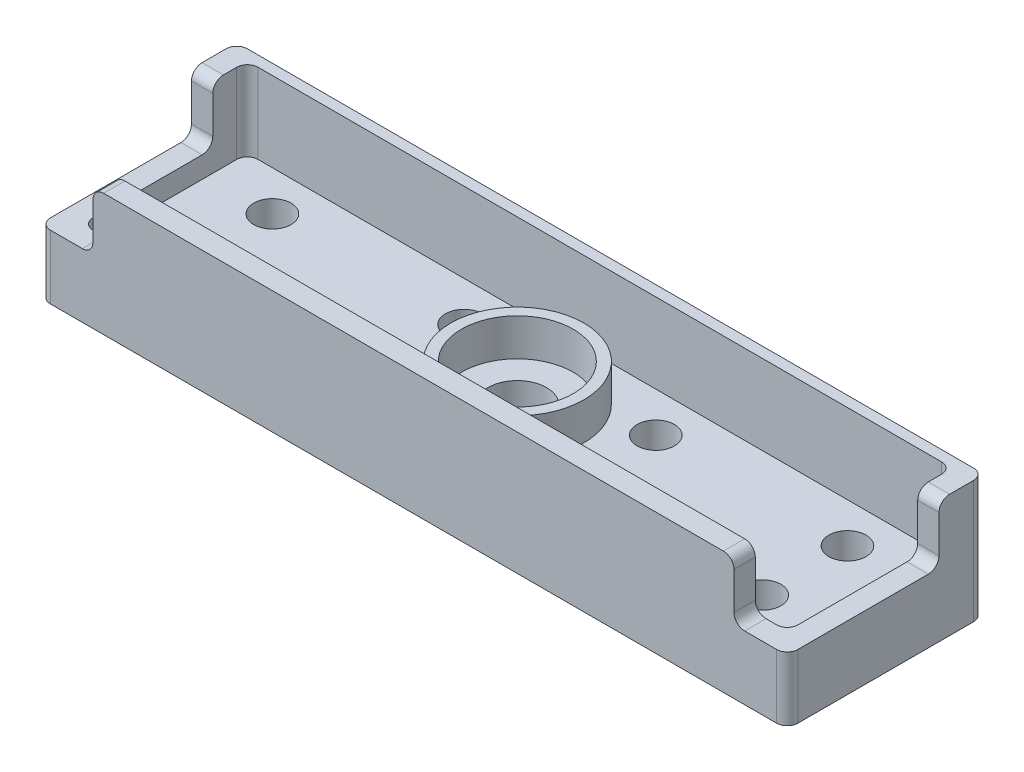
SolidWorks part; units mm, degrees
material "Delrin 2700 NC010, Low Viscosity Acetal Copolymer (SS)"
ref_plane "Front Plane" through (0, 0, 0) normal (0, 0, 1) x (1, 0, 0)
ref_plane "Top Plane" through (0, 0, 0) normal (0, 1, 0) x (1, 0, 0)
ref_plane "Right Plane" through (0, 0, 0) normal (1, 0, 0) x (0, 0, -1)
sketch "Sketch1" plane through (0, 0, 0) normal (0, 1, 0) x (1, 0, 0)
  line L1 (-35.1, -9.25) -> (0, -9.25)
  line L2 (-35.1, -9.25) -> (-35.1, 9.25)
  line L3 (-35.1, 9.25) -> (0, 9.25)
  line L4 (0, -9.25) -> (0, 9.25)
  line L5 (-35.1, -9.25) -> (0, 9.25) construction
  line L6 (-35.1, 9.25) -> (0, -9.25) construction
  point P0 (-17.55, 0)
  point P8 (0, 0)
  dimension "D1" = 35.1
  dimension "D2" = 18.5
extrude "Boss-Extrude1" add sketch "Sketch1" along normal blind 11.5
shell "Shell1" [suppressed] thickness 1
sketch "Sketch7" plane through (0, 11.5, 0) normal (0, 1, 0) x (1, 0, 0)
  line L0 (0, -9.25) -> (0, 9.25) construction
  line L1 (0, -7.25) -> (-33.1, -7.25)
  line L2 (0, -7.25) -> (0, 8.25)
  line L3 (0, 8.25) -> (-33.1, 8.25)
  line L4 (-33.1, -7.25) -> (-33.1, 8.25)
  line L5 (-35.1, -9.25) -> (0, -9.25) construction
  line L6 (0, 9.25) -> (-35.1, 9.25) construction
  line L7 (-35.1, 9.25) -> (-35.1, -9.25) construction
  dimension "D1" = 2
  dimension "D2" = 1
  dimension "D3" = 2
extrude "Cut-Extrude5" cut sketch "Sketch7" against normal offset from surface (7.5 mm away) 4 up to face at (-17.55, 0, 0)
sketch "Sketch2" plane through (0, 0, 0) normal (0, 1, 0) x (-1, 0, 0)
  line L0 (27, 3.5) -> (9, 3.5) construction
  line L2 (27, 3.5) -> (27, -4.5) construction
  line L3 (27, -4.5) -> (9, -4.5) construction
  line L4 (9, -4.5) -> (9, 3.5) construction
  line L5 (27, -0.5) -> (18.8977, -0.5) construction
  line L6 (17.55, -9.25) -> (17.55, 9.25) construction
  line L7 (0, 7.25) -> (0, -8.25) construction
  line L8 (27, -0.5) -> (0, -0.5) construction
  line L9 (0, -9.25) -> (35.1, -9.25) construction
  line L10 (35.1, 9.25) -> (0, 9.25) construction
  circle A0 centre (27, 3.5) radius 1.75
  circle A1 centre (9, 3.5) radius 1.75
  circle A2 centre (27, -4.5) radius 1.75
  circle A3 centre (9, -4.5) radius 1.75
  circle A5 centre (27, 3.5) radius 2.5 construction
  circle A6 centre (27, -4.5) radius 2.5 construction
  circle A7 centre (9, -4.5) radius 2.5 construction
  circle A8 centre (9, 3.5) radius 2.5 construction
  dimension "D1" = 3.5
  dimension "D4" = 9
  dimension "D5" = 5
  dimension "D2" = 18
  dimension "D3" = 8
extrude "Cut-Extrude1" cut sketch "Sketch2" along normal through all
sketch "Sketch3" [suppressed] plane through (0, 5, 0) normal (0, 1, 0) x (1, 0, 0)
  line L1 (-2.9573, -5.1559) -> (2.9865, -5.139)
  line L2 (2.9865, -5.139) -> (5.9438, 0.0169)
  line L3 (5.9438, 0.0169) -> (2.9573, 5.1559)
  line L4 (2.9573, 5.1559) -> (-2.9865, 5.139)
  line L5 (-2.9865, 5.139) -> (-5.9438, -0.0169)
  line L6 (-5.9438, -0.0169) -> (-2.9573, -5.1559)
  circle A0 centre (0, 0) radius 2.6 construction
  circle A1 centre (0, 0) radius 5.1475 construction
  dimension "D1" = 5.2
extrude "Cut-Extrude2" [suppressed] cut sketch "Sketch3" against normal blind 0.5
sketch "Sketch4" plane through (-35.1, 0, 0) normal (-1, 0, 0) x (0, 0, 1)
  line L0 (-9.25, 11.5) -> (9.25, 11.5) construction
  line L1 (-5, 11.5) -> (9.25, 11.5)
  line L3 (-5, 6) -> (9.25, 6)
  line L4 (9.25, 11.5) -> (9.25, 6)
  line L5 (0, 6) -> (0, 0) construction
  line L11 (-9.25, 0) -> (9.25, 0) construction
  line L12 (-5, 6) -> (-5, 11.5)
  dimension "D1" = 5
  dimension "D2" = 5.5
extrude "Cut-Extrude3" cut sketch "Sketch4" against normal offset from surface (5 mm away) 3 up to face at (-33.1, 7.75, -0.5) offset beyond the face yes
mirror "Mirror1" about plane through (0, 0, 0) normal (1, 0, 0) of bodies 105
sketch "Sketch5" plane through (0, 0, 0) normal (0, 1, 0) x (1, 0, 0)
  line L0 (33.1, 0.5) -> (0, 0.5) construction
  line L1 (33.1, 8.25) -> (33.1, -7.25) construction
  line L4 (0, 0.5) -> (0, 0) construction
  circle A0 centre (0, 0.5) radius 2.75
  dimension "D1" = 5.5
extrude "Cut-Extrude4" cut sketch "Sketch5" along normal through all
sketch "Sketch6" plane through (0, 4, 0) normal (0, 1, 0) x (1, 0, 0)
  circle A0 centre (0, 0.5) radius 6.25
  circle A1 centre (0, 0.5) radius 5.25
  circle A2 centre (0, 0.5) radius 2.75 construction
  dimension "D1" = 10.5
  dimension "D2" = 1
extrude "Boss-Extrude2" add sketch "Sketch6" along normal blind 3.5
fillet "Fillet3" radius 1 8 edges at (-34.1, 6, -5) (-34.1, 11.5, -5) (-30.1, 11.5, 8.25) (-30.1, 6, 8.25) (34.1, 11.5, -5) (34.1, 6, -5) (30.1, 11.5, 8.25) (30.1, 6, 8.25)
fillet "Fillet4" [suppressed] radius 0.5
fillet "Fillet5" [suppressed] radius 0.5
fillet "Fillet6" radius 1 8 edges at (-33.1, 7.75, -8.25) (-33.1, 5, 7.25) (-35.1, 3, 9.25) (35.1, 5.75, -9.25) (35.1, 3, 9.25) (33.1, 7.75, -8.25) (33.1, 5, 7.25) (-35.1, 5.75, -9.25)
fillet "Fillet7" [suppressed] radius 1
fillet "Fillet8" [suppressed] radius 1
